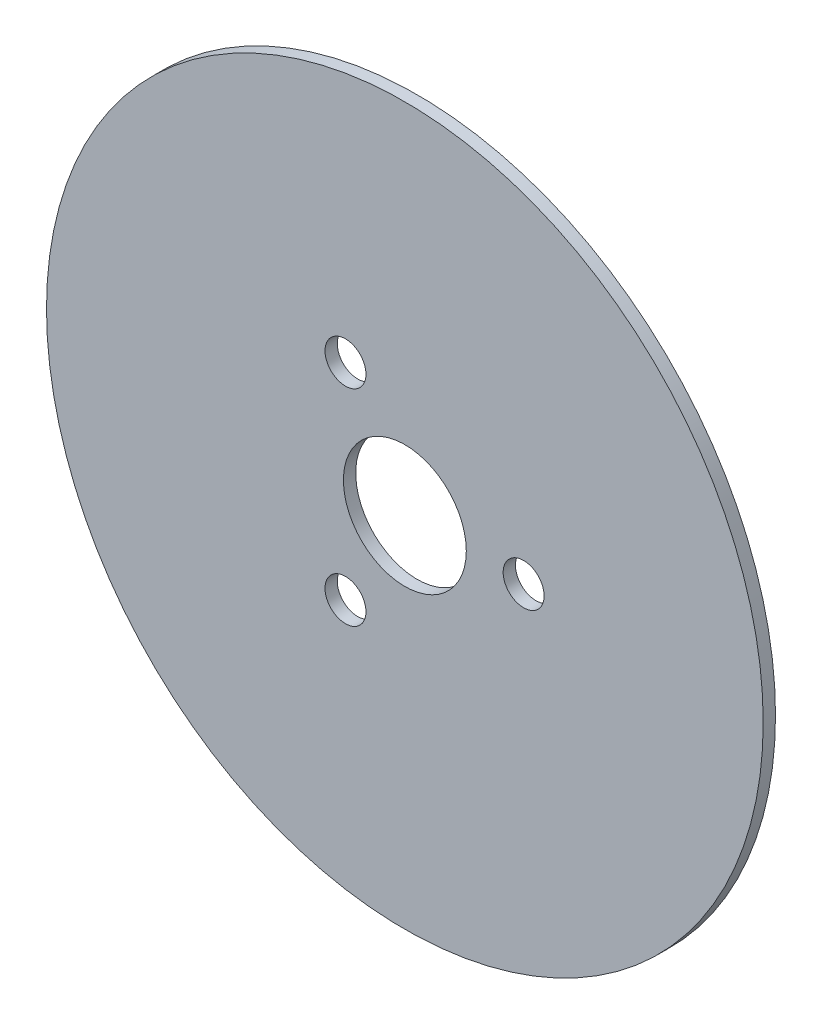
SolidWorks part; units mm, degrees
ref_plane "Front Plane" through (0, 0, 0) normal (0, 0, 1) x (1, 0, 0)
ref_plane "Top Plane" through (0, 0, 0) normal (0, 1, 0) x (1, 0, 0)
ref_plane "Right Plane" through (0, 0, 0) normal (1, 0, 0) x (0, 0, -1)
sketch "Sketch1" plane through (0, 0, 0) normal (0, 0, 1) x (1, 0, 0)
  circle A1 centre (29, 0) radius 5
  circle A2 centre (-14.5, -25.1147) radius 5
  circle A3 centre (-14.5, 25.1147) radius 5
  circle A4 centre (0, 0) radius 15
  circle A5 centre (0, 0) radius 87.5
  point P11 (0, 0)
  dimension "D1" = 10
  dimension "D2" = 29
  dimension "D4" = 30
  dimension "D5" = 175
  dimension "D3" = 3
extrude "Boss-Extrude1" add sketch "Sketch1" along normal blind 3
